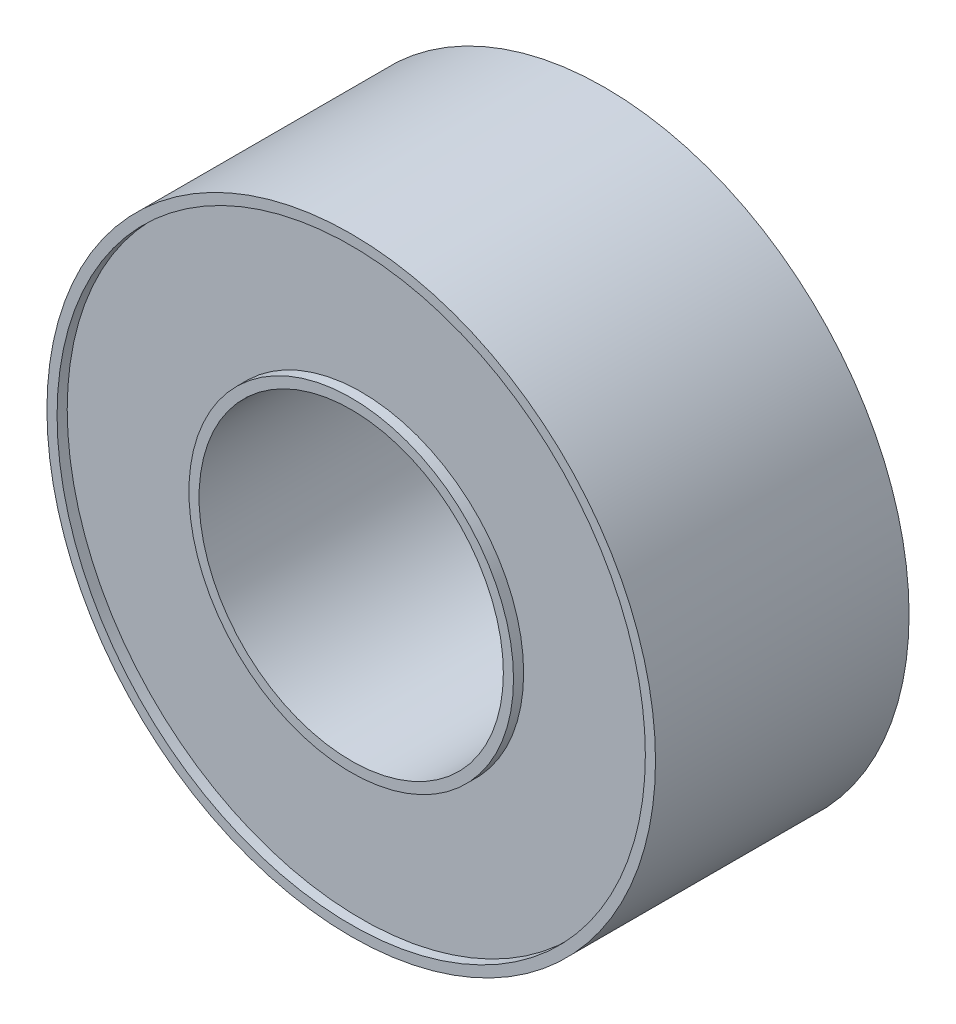
SolidWorks part; units mm, degrees
ref_plane "Alzado" through (0, 0, 0) normal (0, 0, 1) x (1, 0, 0)
ref_plane "Planta" through (0, 0, 0) normal (0, 1, 0) x (1, 0, 0)
ref_plane "Vista lateral" through (0, 0, 0) normal (1, 0, 0) x (0, 0, -1)
sketch "Croquis1" plane through (0, 0, 0) normal (0, 0, 1) x (1, 0, 0)
  circle A0 centre (0, 0) radius 1.5
  circle A1 centre (0, 0) radius 1.6
  circle A2 centre (0, 0) radius 2.9
  circle A3 centre (0, 0) radius 3
  dimension "D1" = 3
  dimension "D2" = 5.8
  dimension "D3" = 6
  dimension "D4" = 3.2
extrude "Saliente-Extruir1" add sketch "Croquis1" along normal blind 2.5 contours A1 A0 | A3 A2
sketch "Croquis2" plane through (0, 0, 0) normal (0, 0, 1) x (1, 0, 0)
  circle A0 centre (0, 0) radius 1.6
  circle A1 centre (0, 0) radius 2.9
extrude "Saliente-Extruir4" add sketch "Croquis2" along normal blind 2.4 contours A1 | A0
sketch "Croquis3" plane through (0, 0, 0) normal (0, 0, -1) x (-1, 0, 0)
  circle A0 centre (0, 0) radius 2.9
  circle A1 centre (0, 0) radius 1.6
  dimension "D1" = 5.8
  dimension "D2" = 3.2
extrude "Cortar-Extruir1" cut sketch "Croquis3" against normal blind 0.1
